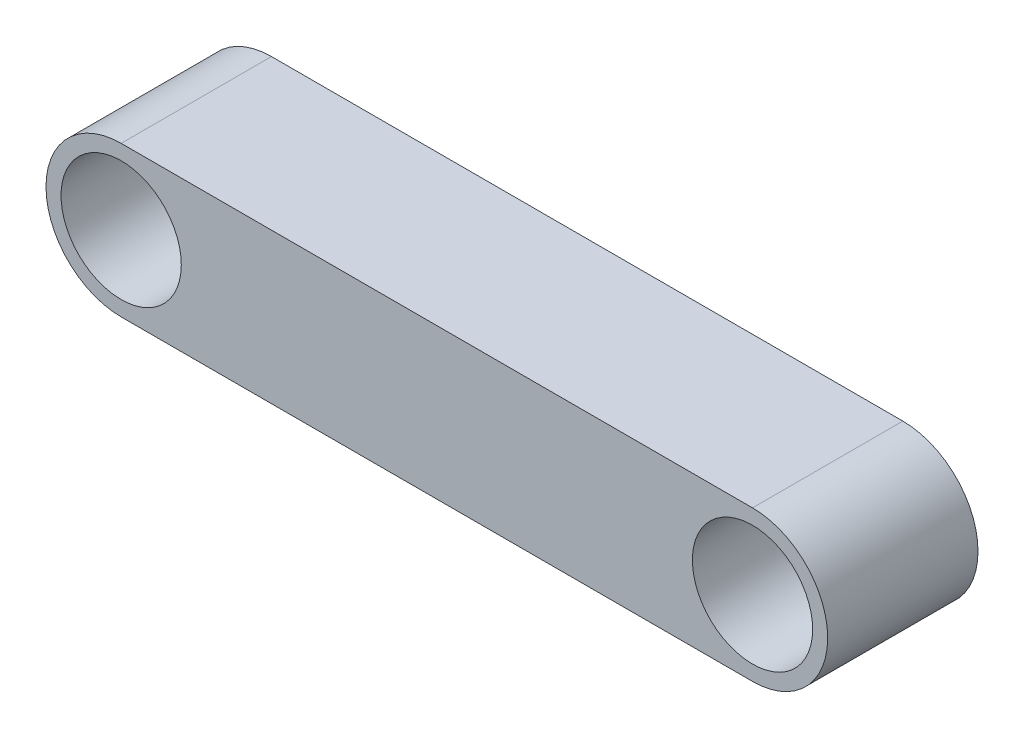
SolidWorks part; units mm, degrees
ref_plane "Front Plane" through (0, 0, 0) normal (0, 0, 1) x (1, 0, 0)
ref_plane "Top Plane" through (0, 0, 0) normal (0, 1, 0) x (1, 0, 0)
ref_plane "Right Plane" through (0, 0, 0) normal (1, 0, 0) x (0, 0, -1)
sketch "Sketch1" plane through (0, 0, 0) normal (0, 0, 1) x (1, 0, 0)
  line L0 (0, 0) -> (42, 0) construction
  line L1 (0, 5) -> (42, 5)
  line L2 (0, -5) -> (42, -5)
  arc A0 (0, 5) -> (0, -5) centre (0, 0) ccw
  arc A1 (42, -5) -> (42, 5) centre (42, 0) ccw
  circle A2 centre (0, 0) radius 4
  circle A3 centre (42, 0) radius 4
  point P3 (21, 0)
  dimension "D1" = 42
extrude "Boss-Extrude1" add sketch "Sketch1" along normal blind 10
